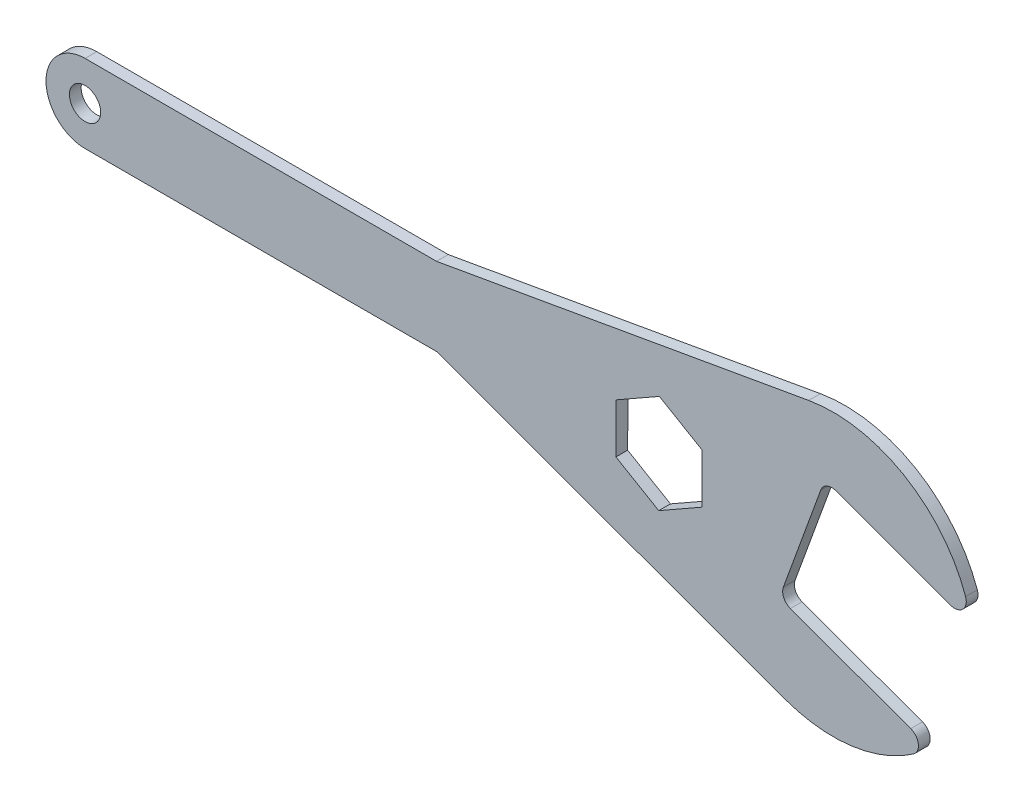
SolidWorks part; units mm, degrees
ref_plane "Front Plane" through (0, 0, 0) normal (0, 0, 1) x (1, 0, 0)
ref_plane "Top Plane" through (0, 0, 0) normal (0, 1, 0) x (1, 0, 0)
ref_plane "Right Plane" through (0, 0, 0) normal (1, 0, 0) x (0, 0, -1)
sketch "Sketch3" plane through (0, 0, 0) normal (0, 0, 1) x (1, 0, 0)
  line L0 (90, 10) -> (0, 10)
  line L1 (0, -10) -> (89.9993, -10)
  line L2 (90, 10) -> (185.2956, 26.8032)
  line L3 (89.9993, -10) -> (179.2342, -42.4788)
  line L4 (216.3788, -34.7148) -> (177.7836, -20.6673)
  line L5 (177.7836, -20.6673) -> (189.4123, 11.2822)
  line L6 (189.4123, 11.2822) -> (227, -2.3986)
  arc A0 (0, 10) -> (0, -10) centre (0, 0) ccw
  arc A1 (185.2956, 26.8032) -> (227, -2.3986) centre (191.5469, -8.6499) cw
  arc A2 (179.2342, -42.4788) -> (216.3788, -34.7148) centre (191.5469, -8.6499) ccw
  dimension "D1" = 20
  dimension "D2" = 100
  dimension "D5" = 36
  dimension "D3" = 34
  dimension "D4" = 170
  dimension "D6" = 237
  dimension "D7" = 160
  dimension "D8" = 40
  dimension "D9" = 20
extrude "Boss-Extrude1" add sketch "Sketch3" along normal blind 3
sketch "Sketch4" plane through (0, 0, 3) normal (0, 0, 1) x (1, 0, 0)
  line L0 (89.9993, -10) -> (179.2342, -42.4788) construction
  line L1 (157.9372, -10.5531) -> (158.0165, 2.1484)
  line L2 (158.0165, 2.1484) -> (147.0563, 8.5677)
  line L3 (147.0563, 8.5677) -> (136.0169, 2.2856)
  line L4 (136.0169, 2.2856) -> (135.9377, -10.4159)
  line L5 (135.9377, -10.4159) -> (146.8978, -16.8352)
  line L6 (146.8978, -16.8352) -> (157.9372, -10.5531)
  line L7 (90, 10) -> (0, 10) construction
  circle A0 centre (0, 0) radius 4
  circle A1 centre (146.9771, -4.1338) radius 11 construction
  arc A2 (0, 10) -> (0, -10) centre (0, 0) ccw construction
  point P13 (135.9773, -4.0651)
  point P14 (157.9769, -4.2024)
  dimension "D1" = 8
  dimension "D2" = 25
  dimension "D3" = 22
  dimension "D4" = 146
extrude "Cut-Extrude1" cut sketch "Sketch4" against normal blind 3
fillet "Fillet1" radius 3 1 edges at (177.7836, -20.6673, 1.5)
fillet "Fillet2" radius 3 1 edges at (189.4123, 11.2822, 1.5)
fillet "Fillet4" radius 3 1 edges at (227, -2.3986, 1.5)
fillet "Fillet5" radius 3 1 edges at (216.3788, -34.7148, 1.5)
ref_plane "Plane1" through (89.9993, -10, 3) normal (0.9397, -0.342, 0) x (0, 0, -1)
